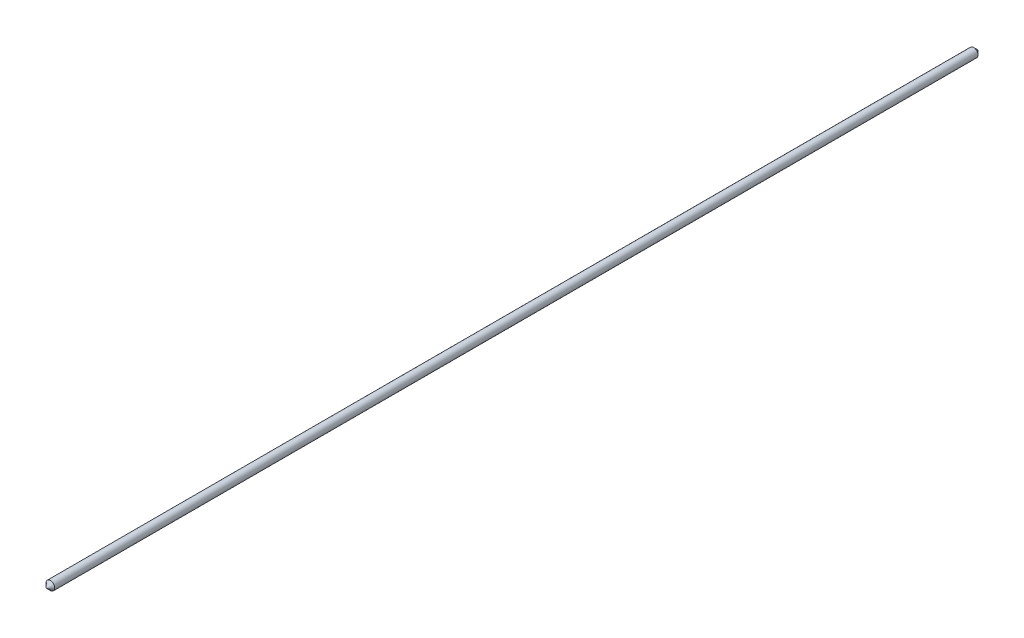
SolidWorks part; units mm, degrees
ref_plane "Front Plane" through (0, 0, 0) normal (0, 0, 1) x (1, 0, 0)
ref_plane "Top Plane" through (0, 0, 0) normal (0, 1, 0) x (1, 0, 0)
ref_plane "Right Plane" through (0, 0, 0) normal (1, 0, 0) x (0, 0, -1)
sketch "Sketch1" plane through (0, 0, 0) normal (1, 0, 0) x (0, 0, -1)
  line L0 (-52.7353, 0) -> (-42.3399, 10.3954)
  line L1 (55, 0) -> (-55, 0) construction
  line L3 (-42.3399, 0) -> (-52.7353, 0)
  line L4 (-42.3399, 10.3954) -> (2157.6601, 10.3954)
  line L5 (2157.6601, 10.3954) -> (2168.0555, 0)
  line L6 (2168.0555, 0) -> (2057.6601, 0)
  line L8 (-42.3399, 0) -> (2057.6601, 0)
  dimension "D1" = 45
  dimension "D2" = 45
  dimension "D3" = 2200
revolve "Revolve1" add sketch "Sketch1" angle 360 about L8
ref_plane "Plane1" through (0, 0, 52.7353) normal (0, 0, 1) x (1, 0, 0)
sketch "Sketch3" plane through (0, 0, 52.7353) normal (0, 0, 1) x (1, 0, 0)
  circle A0 centre (0, 0) radius 8
  dimension "D1" = 16
